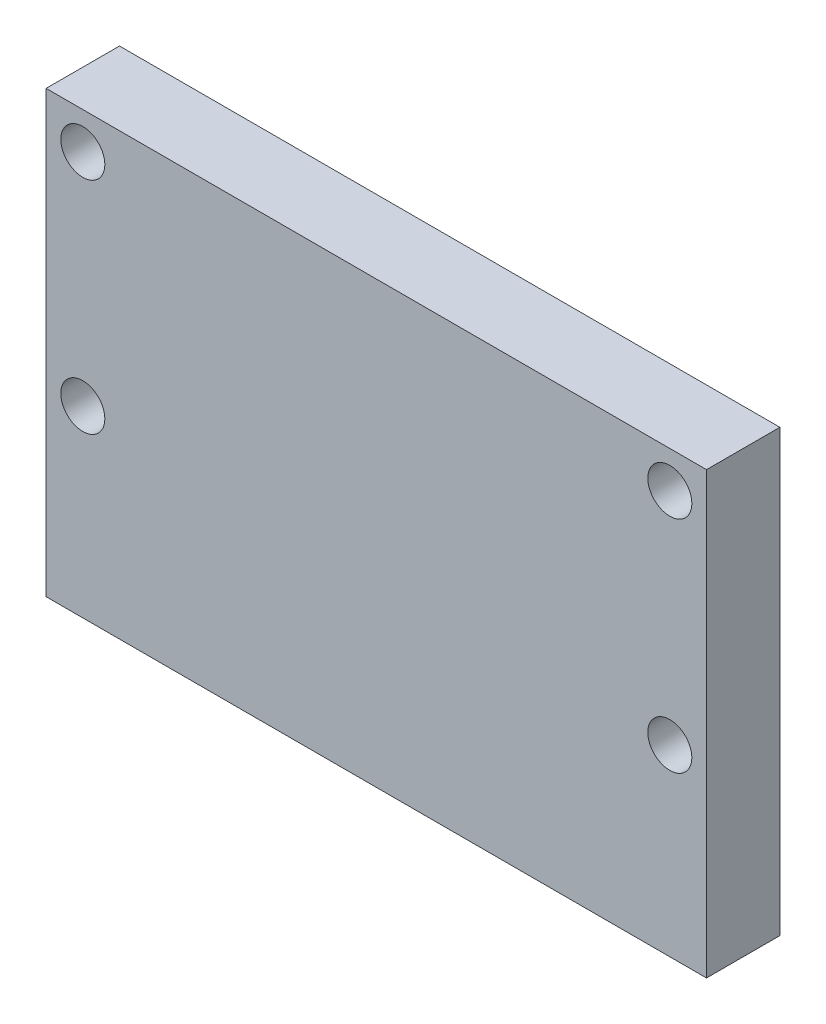
SolidWorks part; units mm, degrees
ref_plane "Front Plane" through (0, 0, 0) normal (0, 0, 1) x (1, 0, 0)
ref_plane "Top Plane" through (0, 0, 0) normal (0, 1, 0) x (1, 0, 0)
ref_plane "Right Plane" through (0, 0, 0) normal (1, 0, 0) x (0, 0, -1)
sketch "Sketch1" plane through (0, 0, 0) normal (0, 0, 1) x (1, 0, 0)
  line L0 (-22.5, -10) -> (-20, -10)
  line L1 (-22.5, 10) -> (22.5, 10)
  line L2 (-22.5, 10) -> (-22.5, -10)
  line L3 (-22.5, -10) -> (-20, -10)
  line L4 (22.5, 10) -> (22.5, -10)
  line L5 (-22.5, 10) -> (-16.875, 7.5) construction
  line L6 (-22.5, -10) -> (-16.875, -7.5) construction
  line L7 (-22.5, 7.5) -> (22.5, 7.5) construction
  line L8 (-22.5, -7.5) -> (-16.875, -7.5) construction
  line L9 (-20, 10) -> (-20, -10) construction
  line L10 (20, 10) -> (20, -10) construction
  line L11 (-22.5, -10) -> (-22.5, -20)
  line L12 (22.5, -10) -> (22.5, -20)
  line L13 (-22.5, -20) -> (22.5, -20)
  line L14 (20, -10) -> (22.5, -10)
  line L15 (20, -10) -> (22.5, -10)
  line L16 (16.875, -7.5) -> (22.5, -7.5) construction
  line L17 (16.875, 7.5) -> (22.5, 10) construction
  line L18 (16.875, -7.5) -> (22.5, -10) construction
  circle A0 centre (-20, 7.5) radius 1.5
  circle A1 centre (-20, -7.5) radius 1.5
  circle A2 centre (20, 7.5) radius 1.5
  circle A3 centre (20, -7.5) radius 1.5
  point P0 (0, 0)
  point P5 (22.5, 0)
  dimension "D7" = 3
  dimension "D8" = 3
  dimension "D9" = 3
  dimension "D10" = 3
  dimension "D1" = 45
  dimension "D2" = 20
  dimension "D3" = 2.5
  dimension "D4" = 2.5
  dimension "D5" = 2.5
  dimension "D6" = 2.5
  dimension "D11" = 10
extrude "Boss-Extrude2" add sketch "Sketch1" along normal blind 5
